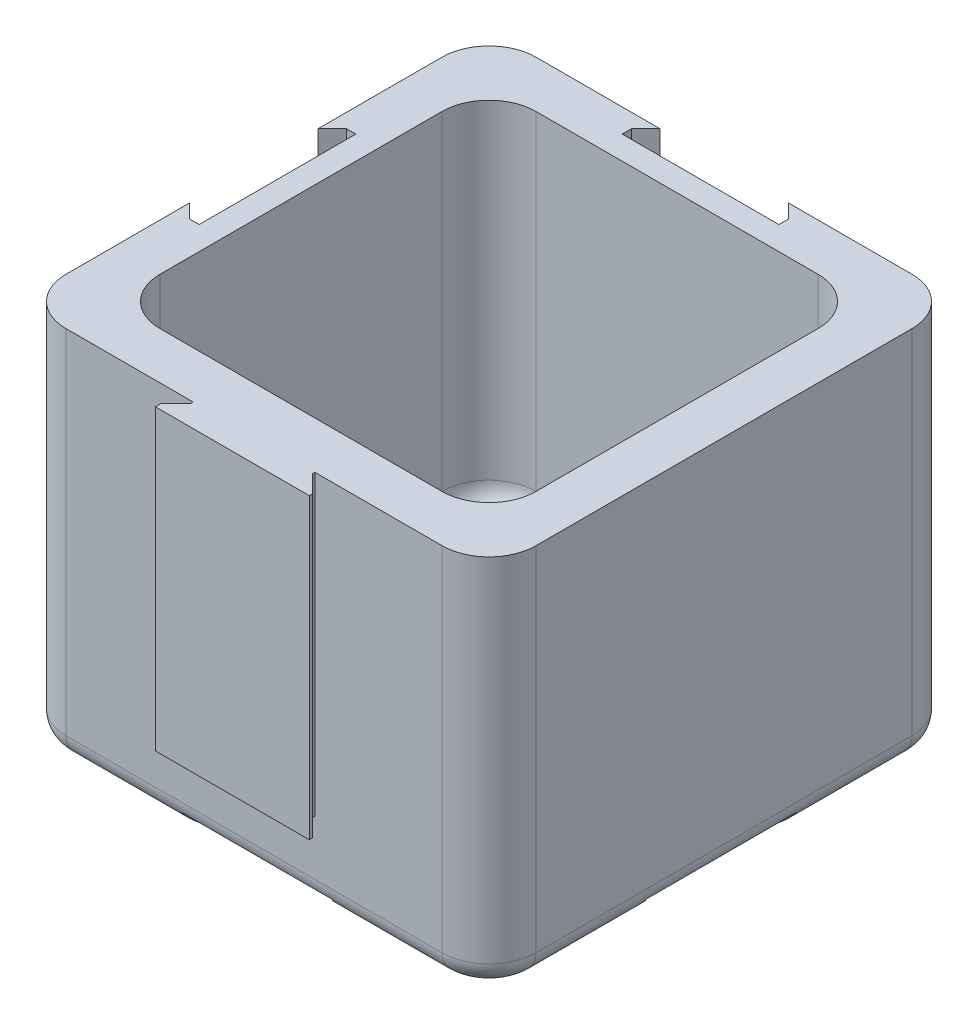
SolidWorks part; units mm, degrees
ref_plane "Front Plane" through (0, 0, 0) normal (0, 0, 1) x (1, 0, 0)
ref_plane "Top Plane" through (0, 0, 0) normal (0, 1, 0) x (1, 0, 0)
ref_plane "Right Plane" through (0, 0, 0) normal (1, 0, 0) x (0, 0, -1)
sketch "Sketch1" plane through (0, 0, 0) normal (0, 1, 0) x (1, 0, 0)
  line L1 (-50, 50) -> (50, 50)
  line L2 (-50, 50) -> (-50, -50)
  line L3 (-50, -50) -> (50, -50)
  line L4 (50, 50) -> (50, -50)
  line L5 (-50, 50) -> (50, -50) construction
  line L6 (-50, -50) -> (50, 50) construction
  point P0 (0, 0)
  dimension "D1" = 100
  dimension "D2" = 100
extrude "Boss-Extrude1" add sketch "Sketch1" along normal blind 80
shell "Shell1" thickness 10
sketch "Sketch2" plane through (0, 80, 0) normal (0, 1, 0) x (1, 0, 0)
  line L0 (-50, 45) -> (-16.6667, 45) construction
  line L1 (-50, 50) -> (-50, -50) construction
  line L2 (50, -50) -> (50, 50) construction
  line L3 (40, 40) -> (-40, 40) construction
  line L4 (-13.6667, 50) -> (-16.6667, 47)
  line L5 (50, 50) -> (-50, 50) construction
  line L6 (-16.6667, 45) -> (16.6667, 45)
  line L7 (16.6667, 47) -> (13.6667, 50)
  line L8 (-13.6667, 50) -> (13.6667, 50)
  line L9 (-16.6667, 47) -> (-16.6667, 45)
  line L10 (16.6667, 47) -> (16.6667, 45)
  line L11 (-16.6667, 45) -> (16.6667, 45) construction
  line L12 (16.6667, 45) -> (50, 45) construction
  point P13 (0, 45)
  dimension "D3" = 100
  dimension "D1" = 5
  dimension "D2" = 45
  dimension "D5" = 2
  dimension "D6" = 2
  dimension "D4" = 33.3333
extrude "Cut-Extrude1" cut sketch "Sketch2" against normal blind 64
sketch "Sketch3" plane through (0, 80, 0) normal (0, 1, 0) x (1, 0, 0)
  line L0 (-13.3667, -50.5) -> (-18.3667, -55.5) construction
  line L2 (-18.3667, -55.5) -> (18.3667, -55.5) construction
  line L3 (18.3667, -55.5) -> (13.3667, -50.5) construction
  line L4 (13.3667, -50.5) -> (12.9424, -50.5) construction
  line L5 (-50, -45) -> (50, -45) construction
  line L6 (-50, 50) -> (-50, -50) construction
  line L7 (50, -50) -> (50, 50) construction
  line L8 (-40, -40) -> (40, -40) construction
  line L9 (-12.9424, -50.5) -> (-16.0667, -53.6243)
  line L11 (-16.0667, -54.9) -> (16.6667, -54.9)
  line L12 (-13.1545, -50.7121) -> (-18.1545, -55.7121) construction
  line L13 (16.3667, -53.5) -> (16.3667, -55.5) construction
  line L14 (16.6667, -54.2243) -> (12.9424, -50.5)
  line L15 (-16.3667, -53.5) -> (-16.3667, -55.5) construction
  line L16 (-16.0667, -53.6243) -> (-16.0667, -54.9)
  line L17 (-50, -50) -> (50, -50) construction
  line L18 (-16.0667, -53.5) -> (-16.0667, -55.5) construction
  line L19 (-13.3667, -50.5) -> (-13.3667, -50) construction
  line L20 (16.6667, -54.2243) -> (16.6667, -54.9)
  line L21 (13.3667, -50.5) -> (13.3667, -50) construction
  line L22 (-12.9424, -50.5) -> (-12.9424, -50)
  line L23 (-12.9424, -50) -> (12.9424, -50)
  line L24 (12.9424, -50) -> (12.9424, -50.5)
  line L25 (-12.9424, -50.5) -> (-13.3667, -50.5) construction
  line L26 (-50, -50) -> (50, -50) construction
  point P4 (0, -50)
  point P36 (0, -50)
  dimension "D1" = 45
  dimension "D2" = 5
  dimension "D3" = 100
  dimension "D5" = 5
  dimension "D7" = 0.6
  dimension "D8" = 0.3
  dimension "D9" = 2
  dimension "D10" = 2
  dimension "D12" = 0.3
  dimension "D4" = 32.7333
  dimension "D13" = 0.5
  dimension "D6" = 0.3
  dimension "D11" = 0.3
extrude "Boss-Extrude2" add sketch "Sketch3" against normal blind 63.4
sketch "Sketch4" plane through (0, 80, 0) normal (0, 1, 0) x (1, 0, 0)
  line L4 (-45, 16.6667) -> (-45, -16.6667)
  line L5 (-47, -16.6667) -> (-50, -13.6667)
  line L6 (-50, 50) -> (-50, -50) construction
  line L7 (-50, -13.6667) -> (-50, 13.6667)
  line L8 (-50, 13.6667) -> (-47, 16.6667)
  line L9 (-47, 16.6667) -> (-45, 16.6667)
  line L10 (-47, -16.6667) -> (-45, -16.6667)
  line L11 (-45, 16.6667) -> (-45, -16.6667) construction
  point P0 (-45, 0)
  dimension "D2" = 45
  dimension "D5" = 2
  dimension "D4" = 2
  dimension "D1" = 33.3333
  dimension "D3" = 5
extrude "Cut-Extrude2" cut sketch "Sketch4" against normal blind 64
sketch "Sketch5" plane through (0, 80, 0) normal (0, 1, 0) x (1, 0, 0)
  line L0 (50.5, 13.6667) -> (50.5, 13.2424) construction
  line L2 (50.5, -13.6667) -> (55.5, -18.6667) construction
  line L3 (55.5, -18.6667) -> (55.5, 18.6667) construction
  line L4 (55.5, 18.6667) -> (50.5, 13.6667) construction
  line L5 (45, 50) -> (45, -50) construction
  line L6 (50, 50) -> (13.6667, 50) construction
  line L7 (12.9424, -50) -> (50, -50) construction
  line L9 (40, -40) -> (40, 40) construction
  line L10 (50.5, -13.2424) -> (53.6243, -16.3667)
  line L11 (53.5, 16.6667) -> (55.5, 16.6667) construction
  line L12 (54.9, -16.3667) -> (54.9, 16.3667)
  line L13 (54.9, -18.6667) -> (54.9, 18.6667) construction
  line L14 (53.6243, 16.3667) -> (50.5, 13.2424)
  line L15 (50.7121, -13.4545) -> (55.7121, -18.4545) construction
  line L16 (55.5, -16.6667) -> (53.5, -16.6667) construction
  line L17 (53.6243, 16.3667) -> (54.9, 16.3667)
  line L18 (54.9, -16.3667) -> (53.6243, -16.3667)
  line L19 (55.5, -16.3667) -> (53.5, -16.3667) construction
  line L20 (53.5, 16.3667) -> (55.5, 16.3667) construction
  line L21 (50, 50) -> (50, -50) construction
  line L22 (12.9424, -50) -> (50, -50) construction
  line L23 (50.5, -13.6667) -> (50, -13.6667) construction
  line L24 (50.5, 13.6667) -> (50, 13.6667) construction
  line L25 (50.5, 13.2424) -> (50, 13.2424)
  line L26 (50, 13.2424) -> (50, -13.2424)
  line L27 (50, -13.2424) -> (50.5, -13.2424)
  line L28 (50.5, -13.2424) -> (50.5, -13.6667) construction
  line L30 (50, -50) -> (50, 50) construction
  point P2 (50, 0)
  dimension "D9" = 2
  dimension "D4" = 32.7333
  dimension "D1" = 5
  dimension "D2" = 45
  dimension "D7" = 0.3
  dimension "D8" = 2
  dimension "D11" = 0.5
  dimension "D3" = 5.5
  dimension "D12" = 0.5
  dimension "D5" = 0.3
  dimension "D6" = 0.6
  dimension "D10" = 0.3
extrude "Boss-Extrude3" [suppressed] add sketch "Sketch5" against normal up to surface (63.4 mm away)
fillet "Fillet1" radius 10 8 edges at (40, 42.5, 40) (50, 40, 50) (50, 40, -50) (40, 42.5, -40) (-40, 42.5, -40) (-50, 40, -50) (-40, 42.5, 40) (-50, 40, 50)
fillet "Fillet2" radius 5 16 edges at (-47.0711, 0, -47.0711) (-50, 0, 0) (-47.0711, 0, 47.0711) (0, 0, 50) (47.0711, 0, 47.0711) (50, 0, 0) (47.0711, 0, -47.0711) (0, 0, -50) (37.0711, 5, 37.0711) (0, 5, 40) (-37.0711, 5, 37.0711) (-40, 5, 0) (-37.0711, 5, -37.0711) (0, 5, -40) (37.0711, 5, -37.0711) (40, 5, 0)
chamfer "Chamfer1" [suppressed] distance 2 angle 45
sketch "Sketch6" plane through (0, 5, 0) normal (0, 1, 0) x (1, 0, 0)
  circle A0 centre (0, 0) radius 12.5
  dimension "D1" = 25
extrude "Cut-Extrude3" cut sketch "Sketch6" against normal through all
sketch "Sketch9" plane through (0, 0, 0) normal (0, -1, 0) x (1, 0, 0)
  line L0 (-6.25, 10.8253) -> (-6.25, 39.5833)
  line L1 (-6.25, 10.8253) -> (6.25, 10.8253)
  line L2 (6.25, 10.8253) -> (6.25, 39.5833)
  line L3 (-6.25, 39.5833) -> (-16.6667, 50)
  line L4 (-40, 50) -> (40, 50) construction
  line L5 (-16.6667, 50) -> (16.6667, 50)
  line L6 (16.6667, 50) -> (6.25, 39.5833)
  line L7 (10.8253, 6.25) -> (39.5833, 6.25)
  line L8 (39.5833, 6.25) -> (50, 16.6667)
  line L9 (50, 40) -> (50, -40) construction
  line L10 (50, 16.6667) -> (50, -16.6667)
  line L11 (50, -16.6667) -> (39.5833, -6.25)
  line L12 (39.5833, -6.25) -> (10.8253, -6.25)
  line L13 (10.8253, -6.25) -> (10.8253, 6.25)
  line L14 (50, 0) -> (-50, 0) construction
  line L15 (-50, -40) -> (-50, 40) construction
  line L16 (0, 50) -> (0, -50) construction
  line L17 (40, -50) -> (-40, -50) construction
  line L18 (-16.6667, -50) -> (16.6667, -50)
  line L19 (-6.25, -39.5833) -> (-16.6667, -50)
  line L20 (-6.25, -10.8253) -> (-6.25, -39.5833)
  line L21 (-6.25, -10.8253) -> (6.25, -10.8253)
  line L22 (6.25, -10.8253) -> (6.25, -39.5833)
  line L23 (16.6667, -50) -> (6.25, -39.5833)
  line L24 (-39.5833, -6.25) -> (-10.8253, -6.25)
  line L25 (-50, -16.6667) -> (-39.5833, -6.25)
  line L26 (-50, 16.6667) -> (-50, -16.6667)
  line L27 (-39.5833, 6.25) -> (-50, 16.6667)
  line L28 (-10.8253, 6.25) -> (-39.5833, 6.25)
  line L29 (-10.8253, -6.25) -> (-10.8253, 6.25)
  circle A0 centre (0, 0) radius 12.5 construction
  point P4 (0, 10.8253)
  point P20 (10.8253, 0)
  dimension "D4" = 33.3333
  dimension "D1" = 12.5
  dimension "D2" = 33.3333
  dimension "D3" = 12.5
extrude "Cut-Extrude4" cut sketch "Sketch9" against normal blind 2.5
fillet "Fillet4" radius 5 8 edges at (-6.25, 1.25, -39.5833) (6.25, 1.25, -39.5833) (-39.5833, 1.25, -6.25) (-39.5833, 1.25, 6.25) (39.5833, 1.25, -6.25) (39.5833, 1.25, 6.25) (6.25, 1.25, 39.5833) (-6.25, 1.25, 39.5833)
sketch "Sketch7" plane through (0, 5, 0) normal (0, 1, 0) x (1, 0, 0)
  line L0 (-7.5, 12.5) -> (-7.5, -12.5)
  line L1 (-12.5, -12.5) -> (12.5, -12.5)
  line L2 (-12.5, -12.5) -> (-12.5, 12.5)
  line L3 (-12.5, 12.5) -> (12.5, 12.5)
  line L4 (12.5, -12.5) -> (12.5, 12.5)
  line L5 (-12.5, -12.5) -> (12.5, 12.5) construction
  line L6 (-12.5, 12.5) -> (12.5, -12.5) construction
  line L7 (-2.5, 12.5) -> (-2.5, -12.5)
  line L8 (2.5, 12.5) -> (2.5, -12.5)
  line L9 (7.5, 12.5) -> (7.5, -12.5)
  line L10 (-12.5, 7.5) -> (12.5, 7.5)
  line L11 (-12.5, 2.5) -> (12.5, 2.5)
  line L12 (-12.5, -2.5) -> (12.5, -2.5)
  line L13 (-12.5, -7.5) -> (12.5, -7.5)
  line L14 (-12.5, -12.5) -> (12.5, -12.5)
  circle A0 centre (0, 0) radius 12.5 construction
  point P0 (0, 0)
  dimension "D5" = 5
  dimension "D1" = 5
  dimension "D3" = 5
  dimension "D4" = 5
  dimension "D6" = 5
  dimension "D2" = 4
extrude "Extrude-Thin1" add sketch "Sketch7" against normal up to surface (2.5 mm away) thin up to face at (34.9246, 2.5, 0) thin type mid plane wall 1.25
equation "\"x\" = 100"
equation "\"y\"= 100"
equation "\"h\"= 80"
equation "\"D1@Sketch1\"=\"x\""
equation "\"D2@Sketch1\"=\"y\""
equation "\"D1@Cut-Extrude1\"=\"h\"*0.8"
equation "\"D5@Sketch3\"=\"D2@Sketch3\""
equation "\"Tolerance\" = 0.3"
equation "\"D6@Sketch3\"=\"Tolerance\""
equation "\"D7@Sketch3\"=\"Tolerance\"*2"
equation "\"D8@Sketch3\"=\"Tolerance\""
equation "\"D1@Boss-Extrude2\"=\"h\"*0.8 - (\"Tolerance\" * 2)"
equation "\"D1@Cut-Extrude2\"=\"h\"*0.8"
equation "\"D6@Sketch5\"=\"Tolerance\"*2"
equation "\"D5@Sketch5\"=\"Tolerance\""
equation "\"D7@Sketch5\"=\"Tolerance\""
equation "\"D1@Boss-Extrude1\"=\"h\""
equation "\"D6@Sketch2\"=\"D5@Sketch2\""
equation "\"Flat\"= 2"
equation "\"D5@Sketch2\"=\"Flat\""
equation "\"D4@Sketch2\"=\"x\"/3"
equation "\"D4@Sketch4\"=\"Flat\""
equation "\"D5@Sketch4\"=\"D4@Sketch4\""
equation "\"D1@Sketch4\"=\"y\"/3"
equation "\"D3@Sketch4\"=5"
equation "\"D9@Sketch3\"=\"Flat\""
equation "\"D10@Sketch3\"=\"D9@Sketch3\""
equation "\"D11@Sketch3\"=\"Tolerance\""
equation "\"D12@Sketch3\"=\"Tolerance\""
equation "\"D8@Sketch5\"=\"Flat\""
equation "\"D9@Sketch5\"=\"D8@Sketch5\""
equation "\"D10@Sketch5\"=\"Tolerance\""
equation "\"D4@Sketch3\"=\"x\"/3 - \"Tolerance\"*2"
equation "\"D4@Sketch5\"=\"y\"/3 - \"Tolerance\"*2"
equation "\"Hole\"= 25"
equation "\"D1@Sketch7\"=\"Hole\"/5"
equation "\"D3@Sketch7\"=\"D1@Sketch7\""
equation "\"D4@Sketch7\"=\"Hole\"/5"
equation "\"D6@Sketch7\"=\"D4@Sketch7\""
equation "\"D5@Extrude-Thin1\"=\"Hole\"/20"
equation "\"D1@Sketch6\"=\"Hole\""
equation "\"D1@Sketch9\"=\"Hole\"/2"
equation "\"D2@Sketch9\"=\"x\"/3"
equation "\"D3@Sketch9\"=\"D1@Sketch9\""
equation "\"D4@Sketch9\"=\"y\"/3"
